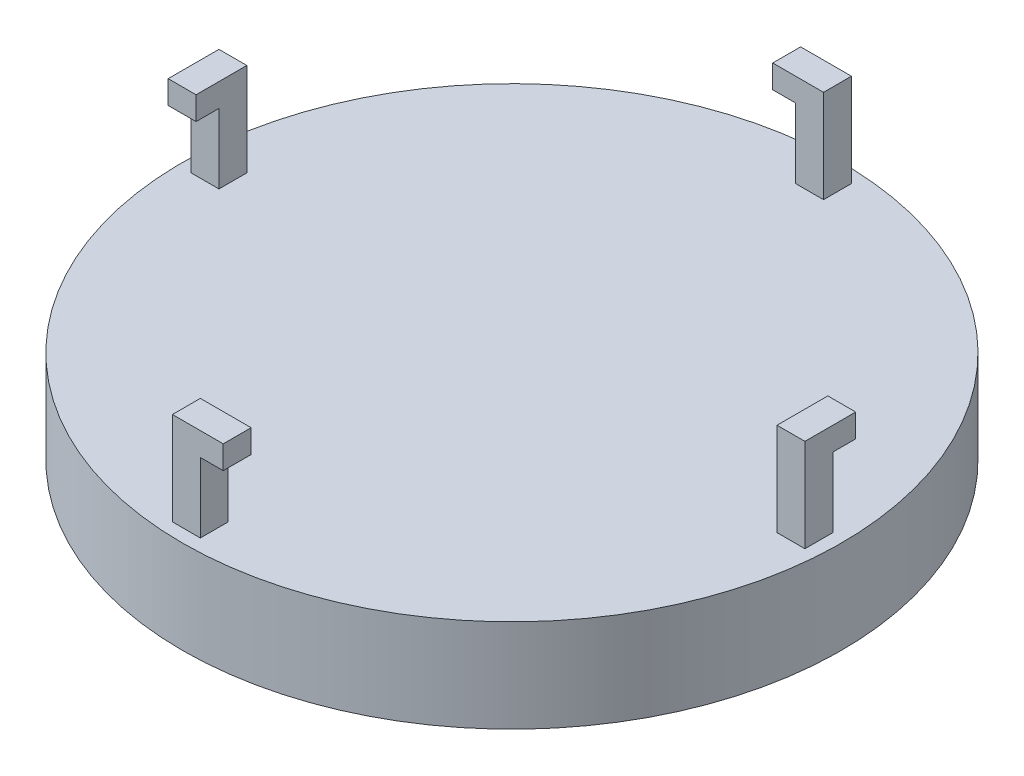
SolidWorks part; units mm, degrees
ref_plane "Front Plane" through (0, 0, 0) normal (0, 0, 1) x (1, 0, 0)
ref_plane "Top Plane" through (0, 0, 0) normal (0, 1, 0) x (1, 0, 0)
ref_plane "Right Plane" through (0, 0, 0) normal (1, 0, 0) x (0, 0, -1)
sketch "Sketch1" plane through (0, 0, 0) normal (0, 1, 0) x (1, 0, 0)
  circle A0 centre (0, 0) radius 45
  dimension "D1" = 90
extrude "Boss-Extrude1" add sketch "Sketch1" along normal blind 12.7
sketch "Sketch2" plane through (0, 12.7, 0) normal (0, 1, 0) x (1, 0, 0)
  line L1 (-43.18, 3.175) -> (-39.37, 3.175)
  line L2 (-43.18, 3.175) -> (-43.18, -0.635)
  line L3 (-43.18, -0.635) -> (-39.37, -0.635)
  line L4 (-39.37, 3.175) -> (-39.37, -0.635)
  line L5 (-43.18, 3.175) -> (-39.37, -0.635) construction
  line L6 (-43.18, -0.635) -> (-39.37, 3.175) construction
  circle A0 centre (0, 0) radius 45 construction
  point P0 (-41.275, 1.27)
  dimension "D1" = 3.81
  dimension "D2" = 3.81
  dimension "D3" = 3.175
  dimension "D4" = 43.18
extrude "Boss-Extrude2" add sketch "Sketch2" along normal blind 12.7
sketch "Sketch3" plane through (0, 0, 0.635) normal (0, 0, 1) x (1, 0, 0)
  line L0 (-43.18, 25.4) -> (-39.37, 25.4) construction
  line L1 (-43.18, 25.4) -> (-39.37, 25.4)
  line L2 (-43.18, 25.4) -> (-43.18, 22.225)
  line L3 (-43.18, 22.225) -> (-39.37, 22.225)
  line L4 (-39.37, 25.4) -> (-39.37, 22.225)
  line L5 (-43.18, 25.4) -> (-39.37, 22.225) construction
  line L6 (-43.18, 22.225) -> (-39.37, 25.4) construction
  line L7 (-39.37, 25.4) -> (-39.37, 12.7) construction
  point P0 (-41.275, 23.8125)
  dimension "D1" = 0
  dimension "D2" = 3.81
  dimension "D3" = 3.175
  dimension "D4" = 0
extrude "Boss-Extrude3" add sketch "Sketch3" along normal blind 3.125
pattern_circular "CirPattern2" count 4 over 360 about axis through (0, 0, 0) along (0, 1, 0) of "Boss-Extrude3", "Boss-Extrude2"
ref_plane "Plane4" through (-45, 0, 0) normal (-1, 0, 0) x (0, 0, 1)
